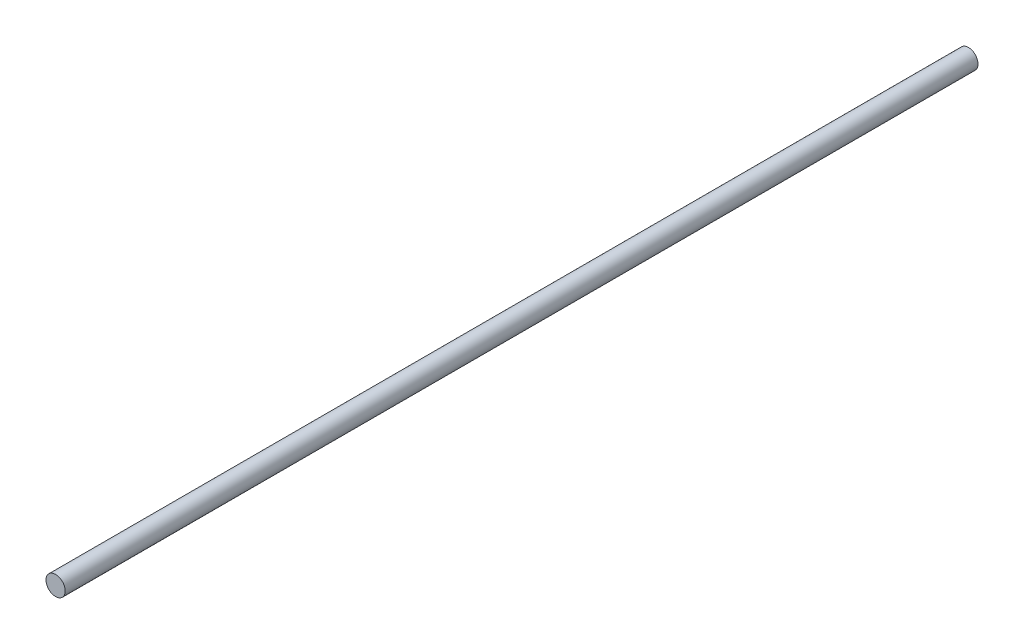
SolidWorks part; units mm, degrees
ref_plane "Front Plane" through (0, 0, 0) normal (0, 0, 1) x (1, 0, 0)
ref_plane "Top Plane" through (0, 0, 0) normal (0, 1, 0) x (1, 0, 0)
ref_plane "Right Plane" through (0, 0, 0) normal (1, 0, 0) x (0, 0, -1)
sketch "Sketch1" plane through (0, 0, 0) normal (0, 0, 1) x (1, 0, 0)
  circle A0 centre (0, 0) radius 5
extrude "Boss-Extrude1" add sketch "Sketch1" along normal blind 475
